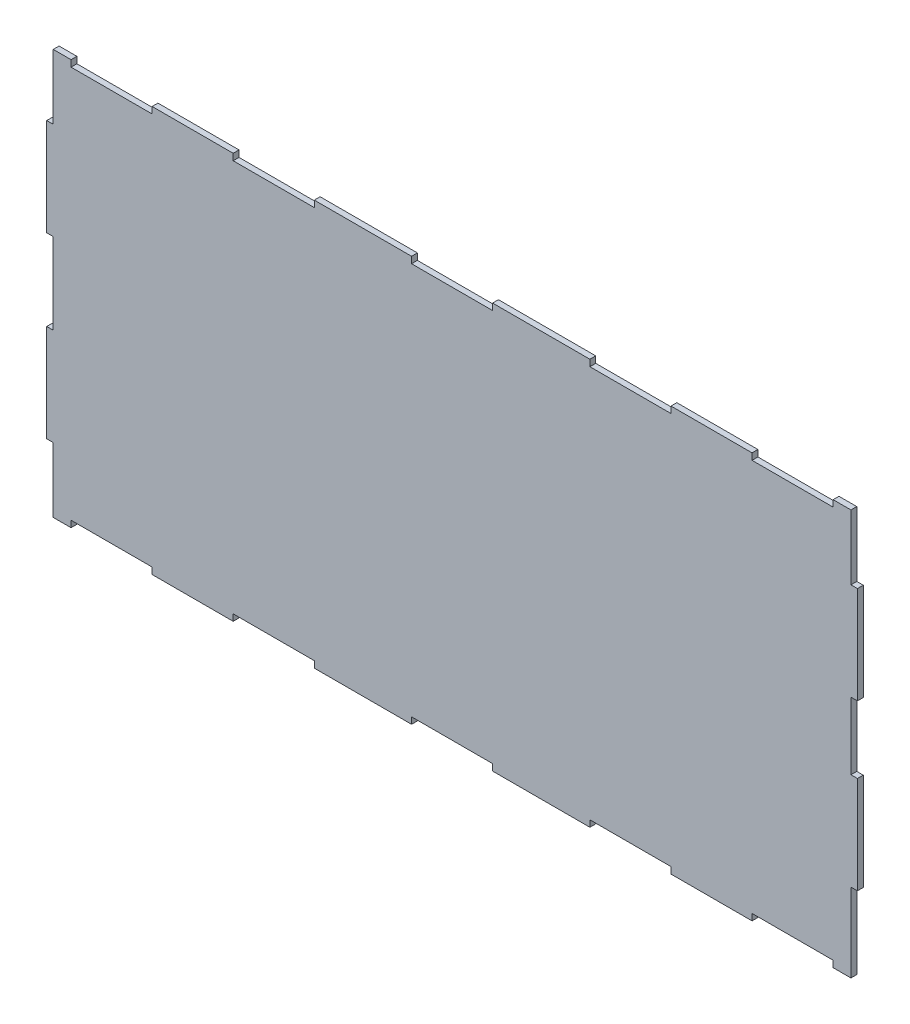
SolidWorks part; units mm, degrees
material "处理板，复杂型"
ref_plane "前视基准面" through (0, 0, 0) normal (0, 0, 1) x (1, 0, 0)
ref_plane "上视基准面" through (0, 0, 0) normal (0, 1, 0) x (1, 0, 0)
ref_plane "右视基准面" through (0, 0, 0) normal (1, 0, 0) x (0, 0, -1)
sketch "草图1" plane through (0, 0, 0) normal (0, 0, 1) x (1, 0, 0)
  line L0 (-28.0519, 0) -> (53.0983, 0) construction
  line L1 (-250, 125) -> (250, 125)
  line L2 (-250, 125) -> (-250, -125)
  line L3 (-250, -125) -> (250, -125)
  line L4 (250, 125) -> (250, -125)
  line L5 (0, 24.8794) -> (0, -28.6642) construction
  dimension "D1" = 500
  dimension "D2" = 250
  dimension "D3" = 250
  dimension "D4" = 125
extrude "凸台-拉伸1" add sketch "草图1" along normal blind 3.6
sketch "草图2" plane through (0, 0, 3.6) normal (0, 0, 1) x (1, 0, 0)
  line L0 (-311.6494, 0) -> (312.6882, 0) construction
  line L1 (0, 183.6134) -> (0, -234.2606) construction
  line L2 (-323.1181, 121) -> (406.0517, 121) construction
  line L3 (296.1915, -121) -> (-344.6593, -121) construction
  line L4 (250, 125) -> (-250, 125) construction
  line L5 (-250, -125) -> (250, -125) construction
  line L6 (0, -183.6134) -> (0, 234.2606) construction
  line L7 (-25, 125) -> (25, 125)
  line L8 (-25, 125) -> (-25, 121)
  line L9 (-25, 121) -> (25, 121)
  line L10 (25, 125) -> (25, 121)
  line L11 (-135, 125) -> (-85, 125)
  line L12 (-135, 125) -> (-135, 121)
  line L13 (-135, 121) -> (-85, 121)
  line L14 (-85, 125) -> (-85, 121)
  line L15 (-235, 125) -> (-185, 125)
  line L16 (-235, 125) -> (-235, 121)
  line L17 (-235, 121) -> (-185, 121)
  line L18 (-185, 125) -> (-185, 121)
  line L19 (85, 125) -> (135, 125)
  line L20 (85, 125) -> (85, 121)
  line L21 (85, 121) -> (135, 121)
  line L22 (135, 125) -> (135, 121)
  line L23 (185, 125) -> (235, 125)
  line L24 (185, 125) -> (185, 121)
  line L25 (185, 121) -> (235, 121)
  line L26 (235, 125) -> (235, 121)
  line L27 (235, -125) -> (235, -121)
  line L28 (185, -121) -> (235, -121)
  line L29 (185, -125) -> (185, -121)
  line L30 (185, -125) -> (235, -125)
  line L31 (135, -125) -> (135, -121)
  line L32 (85, -121) -> (135, -121)
  line L33 (85, -125) -> (85, -121)
  line L34 (85, -125) -> (135, -125)
  line L35 (-185, -125) -> (-185, -121)
  line L36 (-235, -121) -> (-185, -121)
  line L37 (-235, -125) -> (-235, -121)
  line L38 (-235, -125) -> (-185, -125)
  line L39 (-85, -125) -> (-85, -121)
  line L40 (-135, -121) -> (-85, -121)
  line L41 (-135, -125) -> (-135, -121)
  line L42 (-135, -125) -> (-85, -125)
  line L43 (25, -125) -> (25, -121)
  line L44 (-25, -121) -> (25, -121)
  line L45 (-25, -125) -> (-25, -121)
  line L46 (-25, -125) -> (25, -125)
  line L47 (-323.1181, -121) -> (406.0517, -121) construction
  dimension "D1" = 4
  dimension "D2" = 4
  dimension "D3" = 50
  dimension "D4" = 25
  dimension "D5" = 50
  dimension "D6" = 60
  dimension "D7" = 50
  dimension "D8" = 50
  dimension "D9" = 60
  dimension "D10" = 50
  dimension "D11" = 50
  dimension "D12" = 50
extrude "切除-拉伸1" cut sketch "草图2" against normal blind 3.6
sketch "草图3" plane through (0, 0, 3.6) normal (0, 0, 1) x (1, 0, 0)
  line L0 (-246, 195.56) -> (-246, -183.094) construction
  line L1 (246, 211.6619) -> (246, -187.2493) construction
  line L2 (250, -125) -> (250, 125) construction
  line L3 (-250, 125) -> (-250, -125) construction
  line L4 (-276.8358, 0) -> (321.3039, 0) construction
  line L5 (0, 237.0518) -> (0, -225.1956) construction
  line L7 (-250, 25) -> (-246, 25)
  line L8 (-250, 25) -> (-250, -25)
  line L9 (-250, -25) -> (-246, -25)
  line L10 (-246, 25) -> (-246, -25)
  line L11 (-250, 135) -> (-246, 135)
  line L12 (-250, 135) -> (-250, 85)
  line L13 (-250, 85) -> (-246, 85)
  line L14 (-246, 135) -> (-246, 85)
  line L19 (-250, -85) -> (-246, -85)
  line L20 (-250, -85) -> (-250, -135)
  line L21 (-250, -135) -> (-246, -135)
  line L22 (-246, -85) -> (-246, -135)
  line L27 (246, 25) -> (250, 25)
  line L28 (246, 25) -> (246, -16.4485)
  line L29 (246, -16.4485) -> (250, -16.4485)
  line L30 (250, 25) -> (250, -16.4485)
  line L31 (246, -76.4485) -> (250, -76.4485)
  line L32 (246, -76.4485) -> (246, -126.4485)
  line L33 (246, -126.4485) -> (250, -126.4485)
  line L34 (250, -76.4485) -> (250, -126.4485)
  line L39 (246, 135) -> (250, 135)
  line L40 (246, 135) -> (246, 85)
  line L41 (246, 85) -> (250, 85)
  line L42 (250, 135) -> (250, 85)
  dimension "D1" = 4
  dimension "D2" = 4
  dimension "D3" = 41.4485
  dimension "D4" = 25
  dimension "D5" = 50
  dimension "D6" = 60
  dimension "D7" = 50
  dimension "D8" = 60
  dimension "D9" = 50
  dimension "D10" = 25
  dimension "D11" = 50
  dimension "D12" = 60
  dimension "D13" = 60
  dimension "D14" = 50
extrude "切除-拉伸2" cut sketch "草图3" against normal blind 3.6
